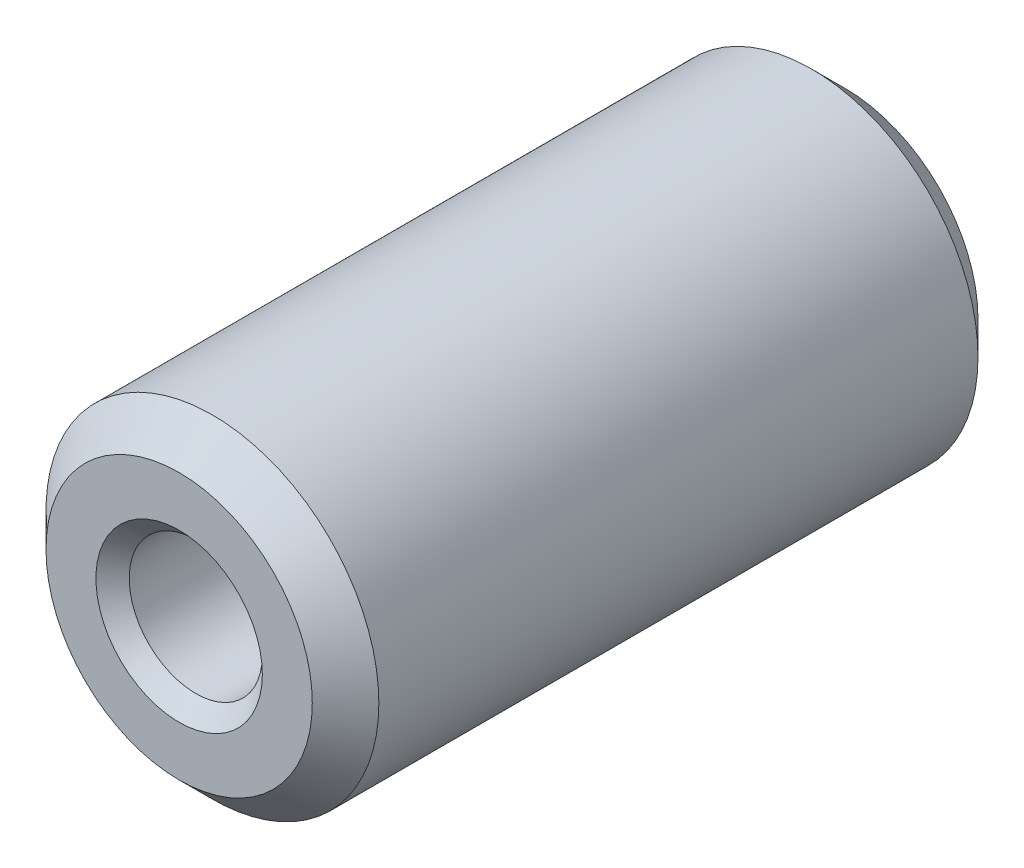
SolidWorks part; units mm, degrees
ref_plane "Plan1" through (0, 0, 0) normal (0, 0, 1) x (1, 0, 0)
ref_plane "Plan2" through (0, 0, 0) normal (0, 1, 0) x (1, 0, 0)
ref_plane "Plan3" through (0, 0, 0) normal (1, 0, 0) x (0, 0, -1)
sketch "Esquisse1" plane through (0, 0, 0) normal (0, 0, 1) x (1, 0, 0)
  circle A0 centre (0, 0) radius 5
  circle A1 centre (0, 0) radius 2
  dimension "D1" = 10
  dimension "D2" = 4
extrude "Base-Extrusion" add sketch "Esquisse1" along normal blind 20
chamfer "Chanfrein1" distance 1 angle 45
chamfer "Chanfrein2" distance 0.5 angle 45
